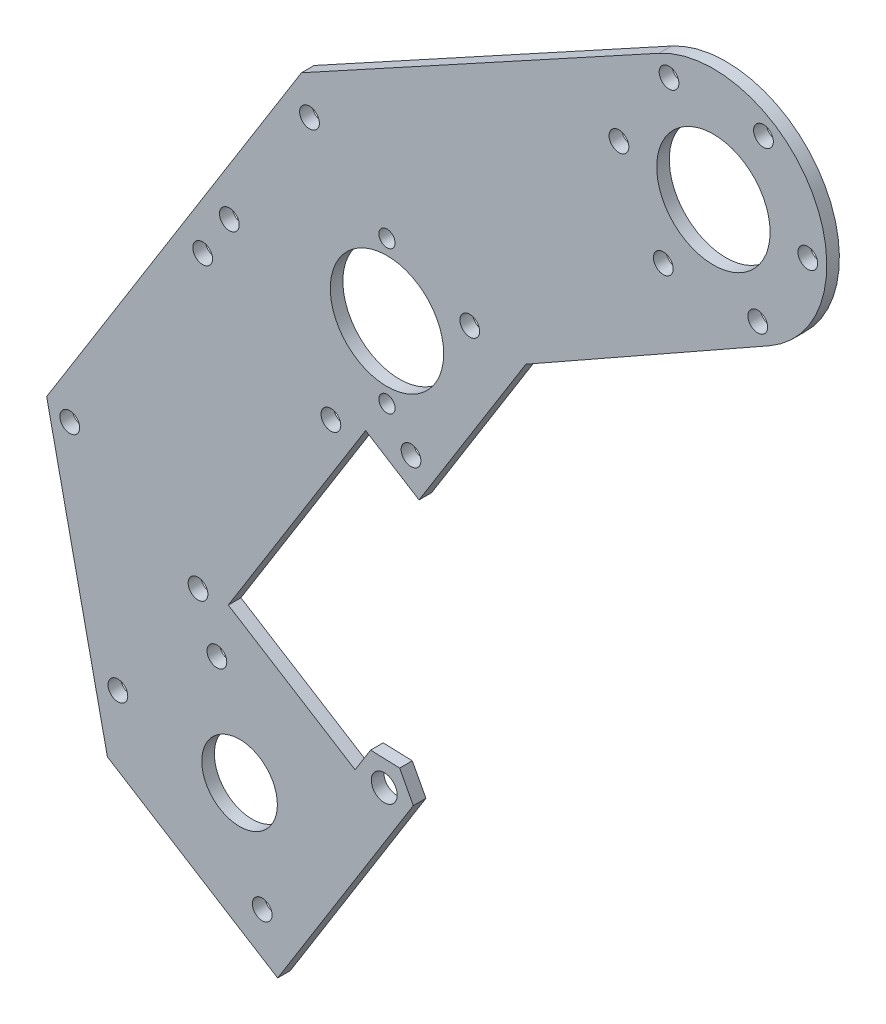
SolidWorks part; units mm, degrees
material "6061 Alloy"
ref_plane "Front Plane" through (0, 0, 0) normal (0, 0, 1) x (1, 0, 0)
ref_plane "Top Plane" through (0, 0, 0) normal (0, 1, 0) x (1, 0, 0)
ref_plane "Right Plane" through (0, 0, 0) normal (1, 0, 0) x (0, 0, -1)
sketch "Sketch1" plane through (0, 0, -14.1946) normal (0, 0, 1) x (1, 0, 0)
  line L0 (-11.4036, 461.0409) -> (18.8813, 509.5069)
  line L1 (-54.3079, 487.8505) -> (-69.6155, 558.824)
  line L2 (8.1111, 516.2368) -> (-23.8465, 536.2061)
  line L3 (10.7592, 591.5868) -> (-157.4902, 322.3315) construction
  line L4 (-11.4036, 461.0409) -> (-54.3079, 487.8505)
  line L5 (-69.6155, 558.824) -> (-5.4017, 661.5875)
  line L6 (-23.8465, 536.2061) -> (10.7592, 591.5868)
  line L8 (-115.7964, 730.5698) -> (48.4493, 627.9377) construction
  line L9 (-142.7163, 687.4889) -> (24.222, 583.1743) construction
  line L10 (51.1419, 626.2552) -> (112.462, 660.9373)
  line L11 (10.7592, 591.5868) -> (24.222, 583.1743)
  line L13 (24.222, 583.1743) -> (51.1419, 626.2552)
  line L16 (-5.4017, 661.5875) -> (84.678, 710.8773)
  line L17 (16.1415, 618.1747) -> (-107.7159, 695.5694) construction
  line L18 (18.8813, 509.5069) -> (22.7847, 515.7536)
  line L19 (-23.8465, 536.2061) -> (-52.9124, 489.691) construction
  line L20 (-4.9986, 524.4287) -> (-34.0645, 477.9135) construction
  line L22 (12.0145, 522.4836) -> (8.1111, 516.2368)
  line L23 (12.0145, 522.4836) -> (19.3423, 522.2277)
  line L24 (19.3423, 522.2277) -> (22.7847, 515.7536)
  line L25 (17.3996, 519.1186) -> (21.0569, 524.9715) construction
  circle A2 centre (16.1415, 618.1747) radius 14.2875
  circle A5 centre (98.3945, 685.8096) radius 14.2875
  arc A7 (112.462, 660.9373) -> (84.678, 710.8773) centre (98.3945, 685.8096) ccw
  circle A8 centre (-107.7159, 695.5694) radius 215.011 construction
  circle A9 centre (-21.0004, 498.8205) radius 9.525
  point P33 (98.3945, 685.8096)
  dimension "D1" = 22.225
  dimension "D2" = 19.05
  dimension "D3" = 7.366
  dimension "D4" = 120
extrude "Boss-Extrude1" add sketch "Sketch1" along normal blind 3.175
sketch "Sketch17" plane through (0, 0, -11.0196) normal (0, 0, 1) x (1, 0, 0)
  line L0 (-4.9986, 524.4287) -> (-34.0645, 477.9135) construction
  line L2 (16.1415, 618.1747) -> (37.6819, 604.7147) construction
  line L11 (-26.7141, 523.5695) -> (-15.2866, 474.0715) construction
  line L12 (24.222, 583.1743) -> (51.1419, 626.2552) construction
  line L13 (37.6819, 604.7147) -> (27.587, 588.5594) construction
  line L14 (27.587, 588.5594) -> (22.2019, 591.9244) construction
  line L15 (22.2019, 591.9244) -> (-28.9566, 623.8918) construction
  line L16 (-5.4017, 661.5875) -> (-69.6155, 558.824) construction
  line L17 (-28.9566, 623.8918) -> (-23.5715, 620.5268) construction
  line L18 (-23.5715, 620.5268) -> (-3.3816, 652.8374) construction
  line L19 (-3.3816, 652.8374) -> (37.0067, 627.6) construction
  line L20 (10.7592, 591.5868) -> (5.3741, 594.9518) construction
  line L21 (5.3741, 594.9518) -> (-31.4748, 535.9811) construction
  line L22 (-31.4748, 535.9811) -> (-51.6648, 503.6705) construction
  line L23 (5.3741, 594.9518) -> (2.0091, 589.5667) construction
  line L24 (-31.4748, 535.9811) -> (-63.7855, 556.1711) construction
  line L25 (2.0091, 589.5667) -> (-30.3015, 609.7566) construction
  circle A1 centre (-21.0004, 498.8205) radius 25.4 construction
  circle A2 centre (15.4568, 516.0095) radius 6.35 construction
  point P32 (-21.0004, 498.8205)
  dimension "D1" = 45
hole_wizard "#10 Clearance Hole2" positions "Sketch20" profile "Sketch21" hole size "#10" standard "ANSI Inch" end condition through all
sketch "Sketch20" plane through (0, 0, -11.0196) normal (0, 0, 1) x (1, 0, 0)
  point P0 (-26.7141, 523.5695)
  point P3 (-15.2866, 474.0715)
  point P24 (-3.3816, 652.8374)
  point P27 (37.0067, 627.6)
  point P30 (22.2019, 591.9244)
  point P33 (-23.5715, 620.5268)
  point P42 (-31.4748, 535.9811)
  point P45 (-63.7855, 556.1711)
  point P48 (-51.6648, 503.6705)
  point P54 (2.0091, 589.5667)
  point P57 (-30.3015, 609.7566)
sketch "Sketch21" plane through (-26.7141, 523.5695, -11.0196) normal (1, 0, 0) x (0, -1, 0)
  line L0 (0, 0) -> (0, 3.175)
  line L1 (0, 3.175) -> (2.4892, 3.175)
  line L2 (2.4892, 3.175) -> (2.4892, 0)
  line L5 (2.4892, 0) -> (0, 0)
  line L11 (0, -6.35) -> (0, 107.95) construction
  dimension "Thru Hole Dia." = 4.9784
  dimension "Thru Hole Depth" = 3.175
sketch "Sketch22" plane through (0, 0, -11.0196) normal (0, 0, 1) x (1, 0, 0)
  line L0 (98.3945, 685.8096) -> (111.0132, 706.0038) construction
  line L2 (111.0132, 706.0038) -> (87.2152, 706.8348) construction
  line L3 (87.2152, 706.8348) -> (74.5965, 686.6407) construction
  line L4 (74.5965, 686.6407) -> (85.7758, 665.6155) construction
  line L5 (85.7758, 665.6155) -> (109.5738, 664.7845) construction
  line L6 (109.5738, 664.7845) -> (122.1925, 684.9786) construction
  line L7 (122.1925, 684.9786) -> (111.0132, 706.0038) construction
  circle A0 centre (98.3945, 685.8096) radius 23.8125 construction
hole_wizard "#10 Clearance Hole3" positions "Sketch23" profile "Sketch24" hole size "#10" standard "ANSI Inch" end condition through all
sketch "Sketch23" plane through (0, 0, -11.0196) normal (0, 0, 1) x (1, 0, 0)
  point P0 (111.0132, 706.0038)
  point P3 (122.1925, 684.9786)
  point P6 (109.5738, 664.7845)
  point P9 (85.7758, 665.6155)
  point P12 (74.5965, 686.6407)
  point P15 (87.2152, 706.8348)
sketch "Sketch24" plane through (111.0132, 706.0038, -11.0196) normal (1, 0, 0) x (0, -1, 0)
  line L0 (0, 0) -> (0, 3.175)
  line L1 (0, 3.175) -> (2.4892, 3.175)
  line L2 (2.4892, 3.175) -> (2.4892, 0)
  line L5 (2.4892, 0) -> (0, 0)
  line L11 (0, -6.35) -> (0, 107.95) construction
  dimension "Thru Hole Dia." = 4.9784
  dimension "Thru Hole Depth" = 3.175
hole_wizard "1/4 Clearance Hole1" positions "Sketch25" profile "Sketch26" hole size "1/4" standard "ANSI Inch" end condition through all
sketch "Sketch25" plane through (0, 0, -11.0196) normal (0, 0, 1) x (1, 0, 0)
  point P0 (15.4568, 516.0095)
sketch "Sketch26" plane through (15.4568, 516.0095, -11.0196) normal (1, 0, 0) x (0, -1, 0)
  line L0 (0, 0) -> (0, 3.175)
  line L1 (0, 3.175) -> (3.2639, 3.175)
  line L2 (3.2639, 3.175) -> (3.2639, 0)
  line L5 (3.2639, 0) -> (0, 0)
  line L11 (0, -6.35) -> (0, 107.95) construction
  dimension "Thru Hole Dia." = 6.5278
  dimension "Thru Hole Depth" = 3.175
hole_wizard "#20 (0.161) Diameter Hole1" positions "Sketch27" profile "Sketch28" hole size "#20" standard "ANSI Inch" end condition through all
sketch "Sketch27" plane through (0, 0, -11.0196) normal (0, 0, 1) x (1, 0, 0)
  point P1 (16.1415, 636.2087)
  point P6 (16.1415, 600.1407)
sketch "Sketch28" plane through (16.1415, 636.2087, -11.0196) normal (1, 0, 0) x (0, -1, 0)
  line L0 (0, 0) -> (0, 3.175)
  line L1 (0, 3.175) -> (2.0447, 3.175)
  line L2 (2.0447, 3.175) -> (2.0447, 0)
  line L5 (2.0447, 0) -> (0, 0)
  line L11 (0, -6.35) -> (0, 107.95) construction
  dimension "Thru Hole Dia." = 4.0894
  dimension "Thru Hole Depth" = 3.175
